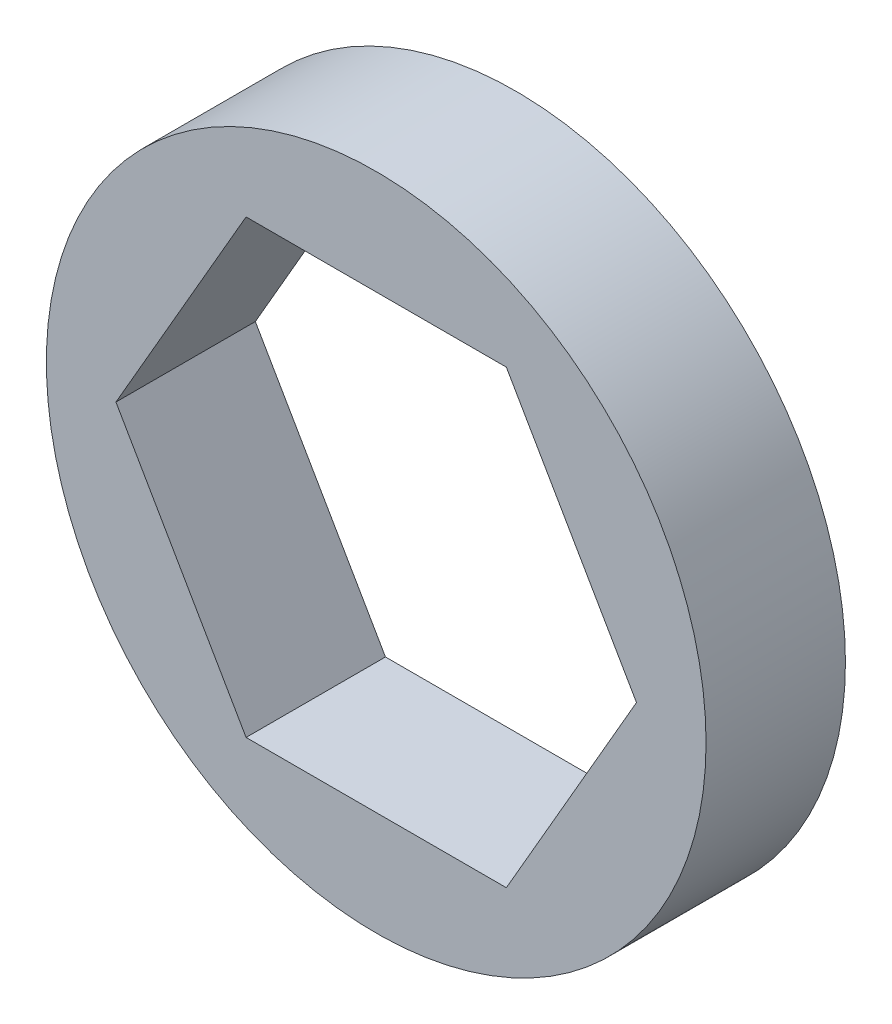
SolidWorks part; units mm, degrees
material "PET"
ref_plane "Front Plane" through (0, 0, 0) normal (0, 0, 1) x (1, 0, 0)
ref_plane "Top Plane" through (0, 0, 0) normal (0, 1, 0) x (1, 0, 0)
ref_plane "Right Plane" through (0, 0, 0) normal (1, 0, 0) x (0, 0, -1)
sketch "Sketch1" plane through (0, 0, 0) normal (0, 0, 1) x (1, 0, 0)
  line L1 (7.5157, 0) -> (3.7578, 6.5087)
  line L2 (3.7578, 6.5087) -> (-3.7578, 6.5087)
  line L3 (-3.7578, 6.5087) -> (-7.5157, 0)
  line L4 (-7.5157, 0) -> (-3.7578, -6.5088)
  line L5 (-3.7578, -6.5088) -> (3.7578, -6.5087)
  line L6 (3.7578, -6.5087) -> (7.5157, 0)
  circle A0 centre (0, 0) radius 6.5087 construction
  circle A1 centre (0, 0) radius 9.525
  dimension "D1" = 13.0175
  dimension "D2" = 19.05
extrude "Boss-Extrude1" add sketch "Sketch1" along normal blind 4.025
